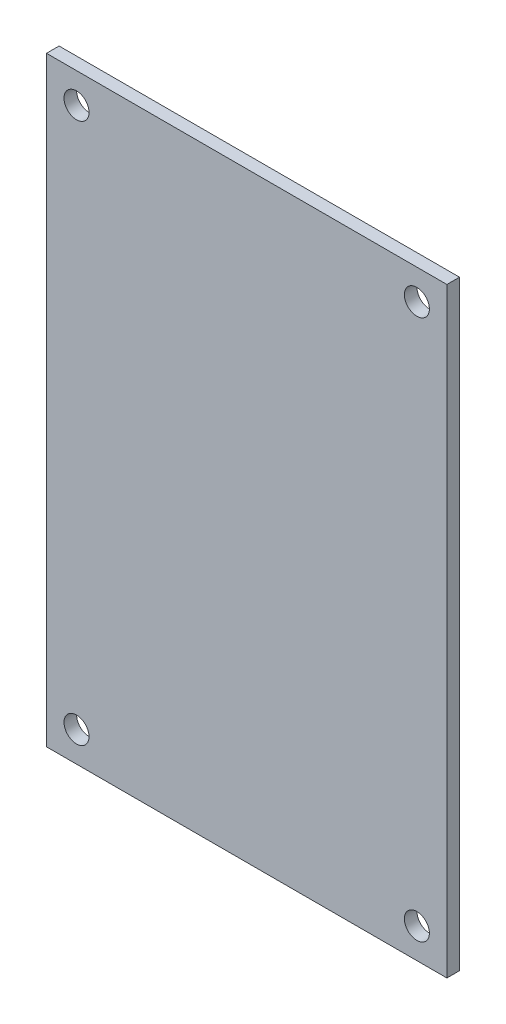
SolidWorks part; units mm, degrees
ref_plane "Front Plane" through (0, 0, 0) normal (0, 0, 1) x (1, 0, 0)
ref_plane "Top Plane" through (0, 0, 0) normal (0, 1, 0) x (1, 0, 0)
ref_plane "Right Plane" through (0, 0, 0) normal (1, 0, 0) x (0, 0, -1)
sketch "Sketch1" plane through (0, 0, 0) normal (0, 0, 1) x (1, 0, 0)
  line L1 (25.4, -38.1) -> (-25.4, -38.1)
  line L2 (25.4, -38.1) -> (25.4, 38.1)
  line L3 (25.4, 38.1) -> (-25.4, 38.1)
  line L4 (-25.4, -38.1) -> (-25.4, 38.1)
  line L5 (25.4, -38.1) -> (-25.4, 38.1) construction
  line L6 (25.4, 38.1) -> (-25.4, -38.1) construction
  point P0 (0, 0)
  dimension "D1" = 50.8
  dimension "D2" = 76.2
extrude "Boss-Extrude1" add sketch "Sketch1" along normal blind 1.6002
sketch "Sketch2" plane through (0, 0, 1.6002) normal (0, 0, 1) x (1, 0, 0)
  line L0 (25.4, 38.1) -> (-25.4, 38.1) construction
  line L1 (-25.4, 38.1) -> (-25.4, -38.1) construction
  line L2 (0, -0.8801) -> (0, 0.8801) construction
  line L3 (0.8801, 0) -> (-0.8801, 0) construction
  circle A0 centre (-21.59, 34.29) radius 1.5875
  circle A2 centre (21.59, 34.29) radius 1.5875
  circle A3 centre (21.59, -34.29) radius 1.5875
  circle A4 centre (-21.59, -34.29) radius 1.5875
  dimension "D1" = 3.175
  dimension "D2" = 3.81
  dimension "D3" = 3.81
extrude "Cut-Extrude1" cut sketch "Sketch2" against normal up to next
